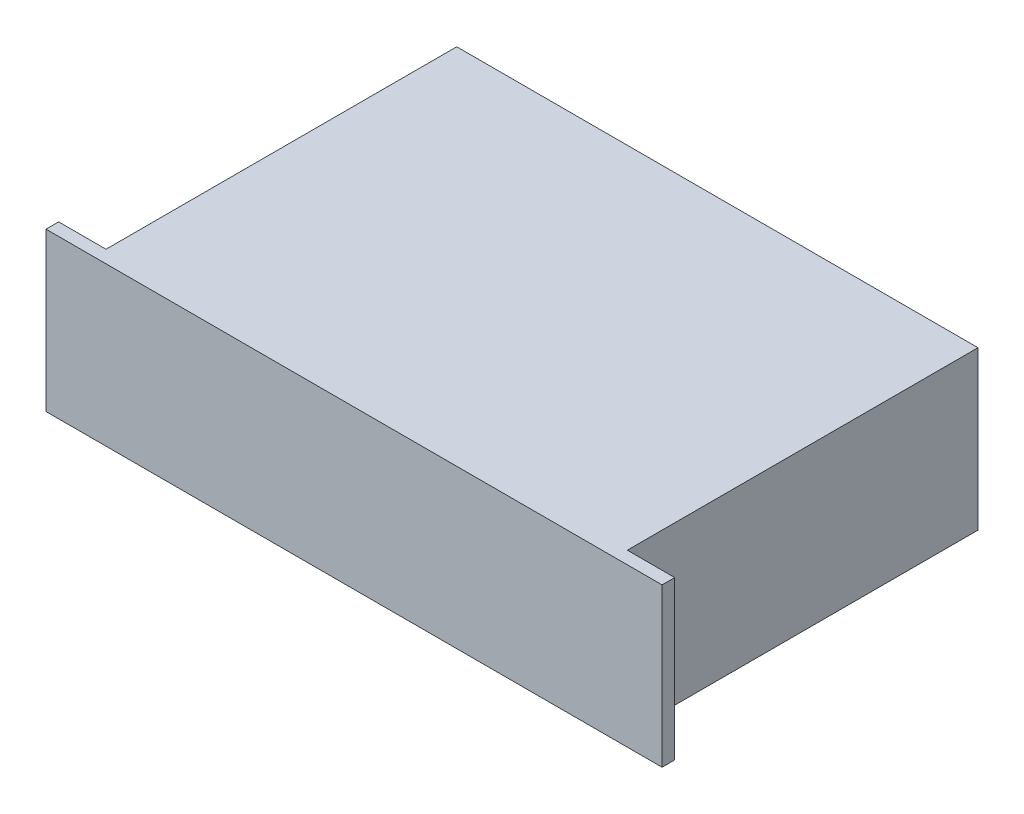
SolidWorks part; units mm, degrees
ref_plane "Alzado" through (0, 0, 0) normal (0, 0, 1) x (1, 0, 0)
ref_plane "Planta" through (0, 0, 0) normal (0, 1, 0) x (1, 0, 0)
ref_plane "Vista lateral" through (0, 0, 0) normal (1, 0, 0) x (0, 0, -1)
sketch "Croquis1" plane through (0, 0, 0) normal (0, 0, 1) x (1, 0, 0)
  line L1 (0, 0) -> (195, 0)
  line L2 (0, 0) -> (0, -50)
  line L3 (0, -50) -> (195, -50)
  line L4 (195, 0) -> (195, -50)
  dimension "D1" = 50
  dimension "D2" = 195
extrude "Saliente-Extruir1" add sketch "Croquis1" along normal blind 4
sketch "Croquis2" plane through (0, 0, 0) normal (0, 0, -1) x (-1, 0, 0)
  line L0 (-97.5, 0) -> (-97.5, -50) construction
  line L1 (-195, 0) -> (0, 0) construction
  line L2 (0, -50) -> (-195, -50) construction
  line L3 (0, 0) -> (0, -50) construction
  line L4 (-180, -50) -> (-15, -50)
  line L5 (-180, -50) -> (-180, 0)
  line L6 (-180, 0) -> (-15, 0)
  line L7 (-15, -50) -> (-15, 0)
  line L8 (-180, -50) -> (-15, 0) construction
  line L9 (-180, 0) -> (-15, -50) construction
  line L10 (-195, -50) -> (-195, 0) construction
  point P6 (-97.5, -25)
  dimension "D1" = 15
  dimension "D2" = 15
extrude "Saliente-Extruir2" add sketch "Croquis2" along normal blind 111
sketch "Croquis3" plane through (0, 0, -111) normal (0, 0, -1) x (-1, 0, 0)
  line L0 (-97.5, 0) -> (-97.5, -50) construction
  line L1 (-15, 0) -> (-180, 0) construction
  line L2 (-180, -50) -> (-15, -50) construction
  line L4 (-142.6287, -30.5652) -> (-52.3713, -30.5652)
  line L5 (-142.6287, -30.5652) -> (-142.6287, -19.4348)
  line L6 (-142.6287, -19.4348) -> (-52.3713, -19.4348)
  line L7 (-52.3713, -30.5652) -> (-52.3713, -19.4348)
  line L8 (-142.6287, -30.5652) -> (-52.3713, -19.4348) construction
  line L9 (-142.6287, -19.4348) -> (-52.3713, -30.5652) construction
  point P6 (-97.5, -25)
extrude "Cortar-Extruir1" cut sketch "Croquis3" against normal blind 10
